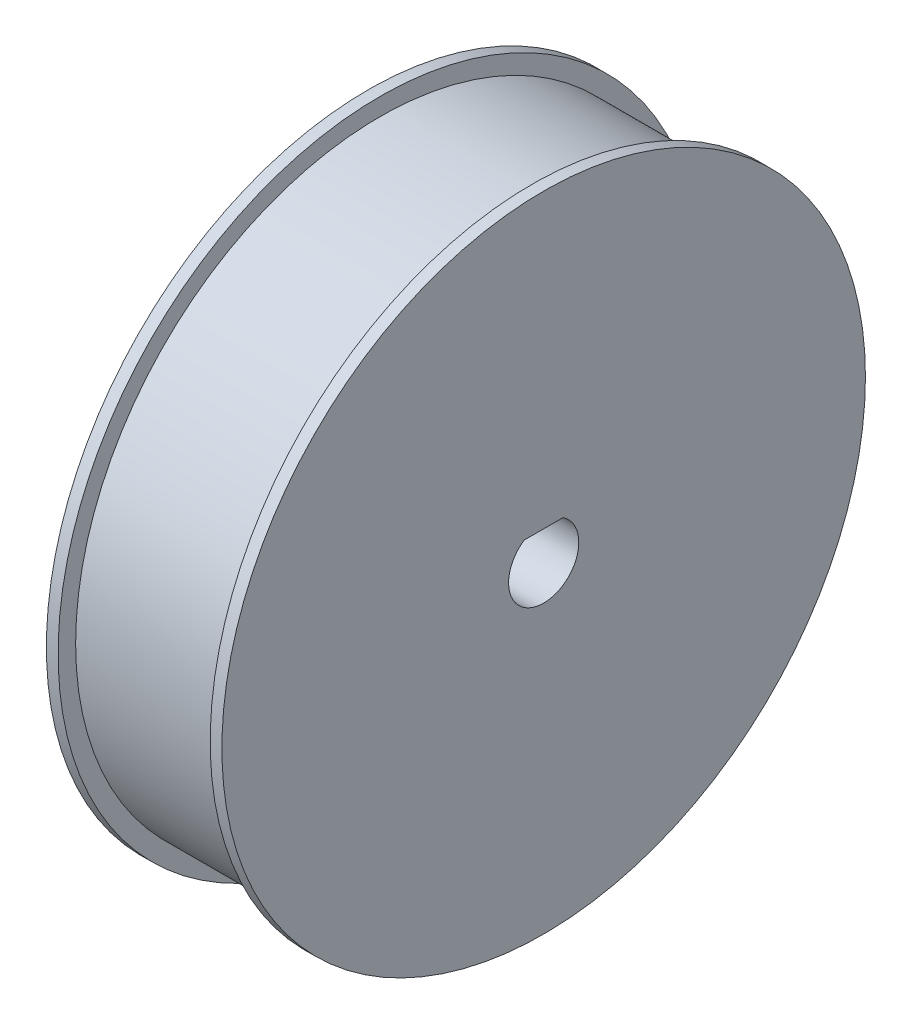
SolidWorks part; units mm, degrees
ref_plane "Plan de face" through (0, 0, 0) normal (0, 0, 1) x (1, 0, 0)
ref_plane "Plan de dessus" through (0, 0, 0) normal (0, 1, 0) x (1, 0, 0)
ref_plane "Plan de droite" through (0, 0, 0) normal (1, 0, 0) x (0, 0, -1)
sketch "Esquisse1" plane through (0, 0, 0) normal (1, 0, 0) x (0, 0, -1)
  line L0 (-1.6583, 2.5) -> (1.6583, 2.5)
  line L1 (0, 0) -> (0, 4.7784) construction
  arc A0 (-1.6583, 2.5) -> (1.6583, 2.5) centre (0, 0) ccw
  circle A1 centre (0, 0) radius 27.5
  point P6 (0, 3)
  dimension "D1" = 6
  dimension "D3" = 55
  dimension "D2" = 0.5
extrude "BASE" add sketch "Esquisse1" along normal blind 10 and the other way blind 5
sketch "Esquisse4" plane through (0, 0, 0) normal (1, 0, 0) x (0, 0, -1)
  circle A0 centre (0, 0) radius 26
  circle A1 centre (0, 0) radius 27.5
  dimension "D1" = 52
extrude "VIDE PNEU" cut sketch "Esquisse4" against normal blind 4 and the other way blind 9
